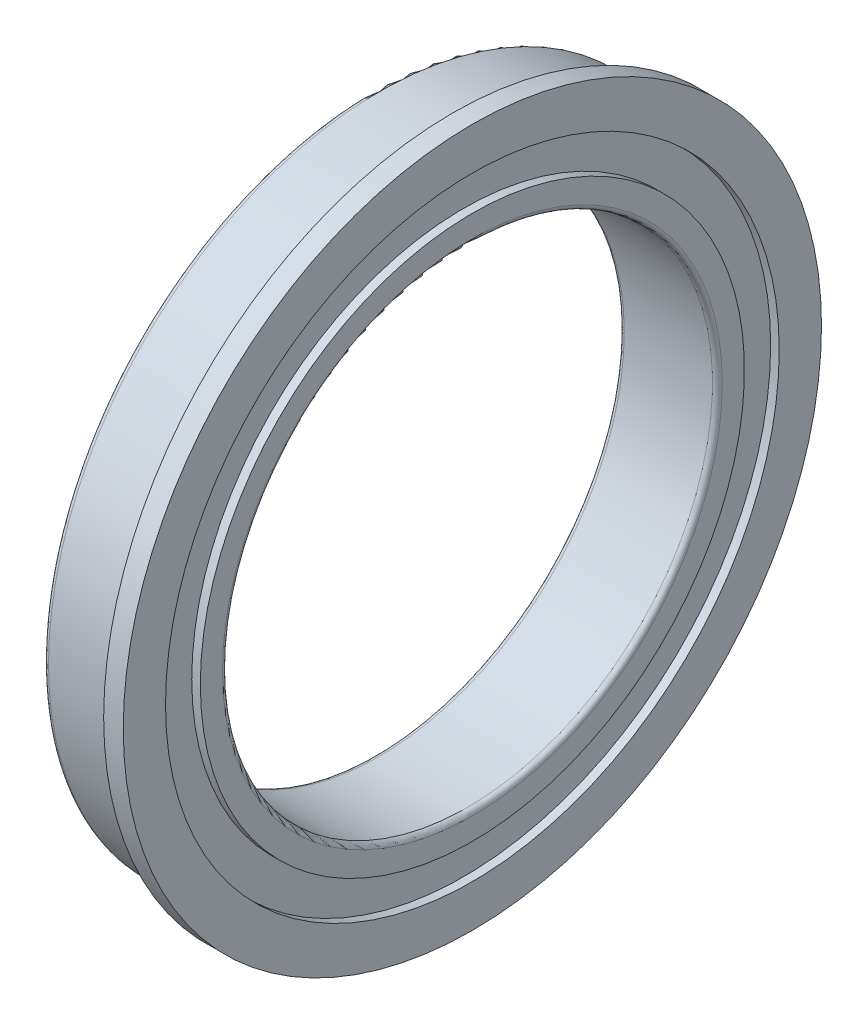
SolidWorks part; units mm, degrees
material "炭素鋼(普通)"
ref_plane "Front Plane" through (0, 0, 0) normal (0, 0, 1) x (1, 0, 0)
ref_plane "Top Plane" through (0, 0, 0) normal (0, 1, 0) x (1, 0, 0)
ref_plane "Right Plane" through (0, 0, 0) normal (1, 0, 0) x (0, 0, -1)
sketch "Sketch1" plane through (0, 0, 0) normal (0, 0, 1) x (1, 0, 0)
  line L0 (-3.2, 0) -> (0.8, 0) construction
  line L1 (0, 13.7) -> (0, 14.25)
  line L2 (0, 14.25) -> (0.8, 14.25)
  line L3 (0.8, 14.25) -> (0.8, 12.525)
  line L4 (0.8, 10) -> (-3.2, 10)
  line L5 (-3.2, 10) -> (-3.2, 11.105)
  line L6 (-3.2, 13.5) -> (-0.2, 13.5)
  line L7 (-3.2, 12.525) -> (-2.85, 12.525)
  line L8 (-2.85, 12.525) -> (-2.85, 11.105)
  line L9 (-2.85, 11.105) -> (-3.2, 11.105)
  line L10 (0.8, 12.525) -> (0.45, 12.525)
  line L11 (0.45, 12.525) -> (0.45, 11.105)
  line L12 (0.45, 11.105) -> (0.8, 11.105)
  line L13 (-3.2, 12.525) -> (-3.2, 13.5)
  line L14 (0.8, 11.105) -> (0.8, 10)
  arc A0 (-0.2, 13.5) -> (0, 13.7) centre (0, 13.5) ccw
  dimension "FIX_1" = 0.2
  dimension "D_s" = 20
  dimension "C" = 0.8
  dimension "MSM_2" = 22.21
  dimension "MSM_1" = 25.05
  dimension "D" = 27
  dimension "D1." = 28.5
  dimension "B" = 4
  dimension "MSM_3" = 0.35
revolve "Revolve1" add sketch "Sketch1" angle 360 about L0
fillet "Fillet1" radius 0.2 3 edges at (0.8, 0, 10) (-3.2, 0, 10) (-3.2, 0, 13.5)
